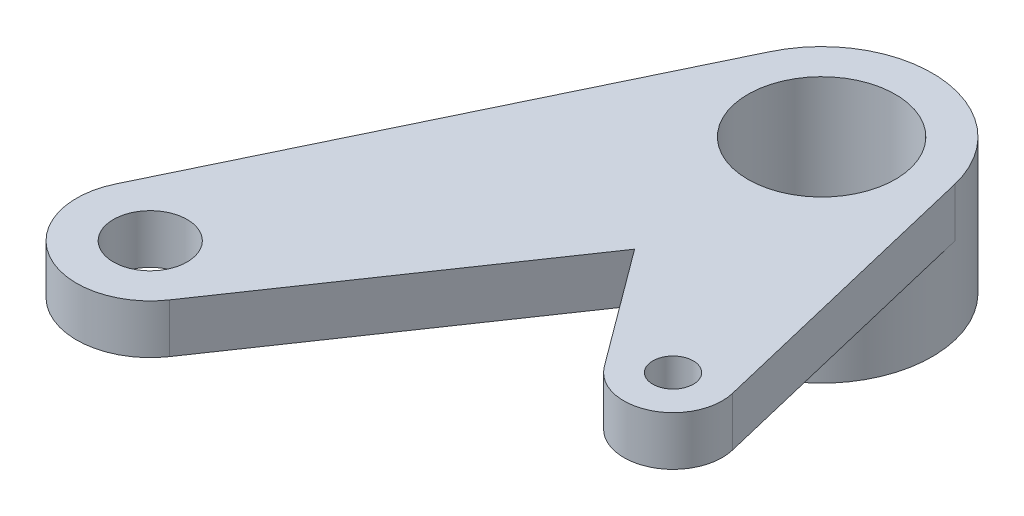
SolidWorks part; units mm, degrees
ref_plane "前视基准面" through (0, 0, 0) normal (0, 0, 1) x (1, 0, 0)
ref_plane "上视基准面" through (0, 0, 0) normal (0, 1, 0) x (1, 0, 0)
ref_plane "右视基准面" through (0, 0, 0) normal (1, 0, 0) x (0, 0, -1)
sketch "草图1" plane through (0, 0, 0) normal (0, 1, 0) x (1, 0, 0)
  line L0 (0, 0) -> (-20, -34.641) construction
  line L1 (0, 0) -> (10.5655, -22.6577) construction
  line L2 (0, 0) -> (0, -52.8876) construction
  line L3 (-8.1098, 3.9028) -> (-25.4065, -32.0392)
  line L4 (0.303, -15.5263) -> (-15.0435, -38.0223)
  line L5 (8.7527, 2.0954) -> (14.4555, -21.7264)
  line L7 (7.3516, -25.0391) -> (0.303, -15.5263)
  arc A0 (7.3516, -25.0391) -> (14.4555, -21.7264) centre (10.5655, -22.6577) ccw
  arc A1 (8.7527, 2.0954) -> (-8.1098, 3.9028) centre (0, 0) ccw
  arc A2 (-25.4065, -32.0392) -> (-15.0435, -38.0223) centre (-20, -34.641) ccw
  dimension "D1" = 25
  dimension "D2" = 18
  dimension "D6" = 12
  dimension "D8" = 8
  dimension "D3" = 55
  dimension "D4" = 40
  dimension "D5" = 30
extrude "凸台-拉伸1" add sketch "草图1" along normal blind 4
sketch "草图3" plane through (0, 4, 0) normal (0, 1, 0) x (1, 0, 0)
  circle A0 centre (0, 0) radius 9
extrude "凸台-拉伸2" add sketch "草图3" against normal blind 11
sketch "草图4" plane through (0, 4, 0) normal (0, 1, 0) x (1, 0, 0)
  circle A0 centre (-20, -34.641) radius 3
  dimension "D1" = 6
extrude "切除-拉伸1" cut sketch "草图4" against normal through all
hole_wizard "M4 螺纹孔1" positions "草图9" profile "草图8" tap size "M4" standard "GB" end condition through all
sketch "草图9" plane through (0, 4, 0) normal (0, 1, 0) x (1, 0, 0)
  point P0 (10.5655, -22.6577)
sketch "草图8" plane through (10.5655, 4, 22.6577) normal (1, 0, 0) x (0, 0, 1)
  line L0 (0, 0) -> (0, 11)
  line L1 (0, 11) -> (1.65, 11)
  line L2 (1.65, 11) -> (1.65, 0)
  line L5 (1.65, 0) -> (0, 0)
  line L11 (0, -6.35) -> (0, 107.95) construction
  dimension "通孔螺纹孔钻头直径" = 3.3
  dimension "通孔螺纹孔钻头深度" = 11
cosmetic thread "孔螺蚊线1" parameters "D2"=4
sketch "草图10" plane through (0, 4, 0) normal (0, 1, 0) x (1, 0, 0)
  circle A0 centre (0, 0) radius 6
  dimension "D1" = 12
extrude "切除-拉伸2" cut sketch "草图10" against normal blind 10
sketch "草图11" plane through (0, -7, 0) normal (0, -1, 0) x (1, 0, 0)
  circle A0 centre (0, 0) radius 5.5
  dimension "D1" = 11
extrude "切除-拉伸3" cut sketch "草图11" against normal through all
scale "Scale1" scale about centroid uniform scaling yes scale factor 2
